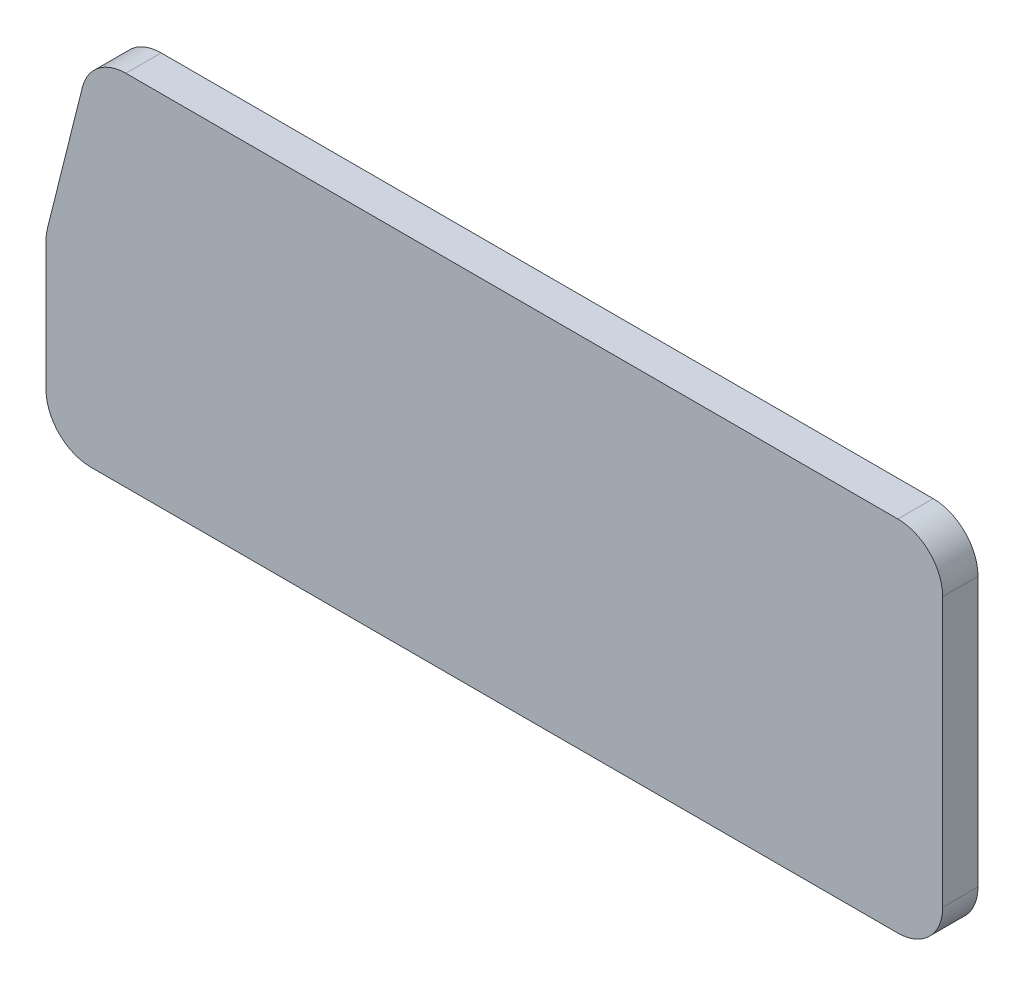
SolidWorks part; units mm, degrees
material "Oak"
ref_plane "Front Plane" through (0, 0, 0) normal (0, 0, 1) x (1, 0, 0)
ref_plane "Top Plane" through (0, 0, 0) normal (0, 1, 0) x (1, 0, 0)
ref_plane "Right Plane" through (0, 0, 0) normal (1, 0, 0) x (0, 0, -1)
sketch "Sketch1" plane through (0, 0, 0) normal (0, 0, 1) x (1, 0, 0)
  line L0 (-63.5, 0) -> (-57.15, 25.4)
  line L1 (-63.5, -25.4) -> (63.5, -25.4)
  line L2 (-63.5, -25.4) -> (-63.5, 0)
  line L3 (-57.15, 25.4) -> (63.5, 25.4)
  line L4 (63.5, -25.4) -> (63.5, 25.4)
  line L5 (-63.5, -25.4) -> (63.5, 25.4) construction
  line L6 (-57.7273, 23.0909) -> (63.5, -25.4) construction
  point P0 (0, 0)
  dimension "D1" = 50.8
  dimension "D2" = 127
  dimension "D3" = 6.35
extrude "Boss-Extrude1" add sketch "Sketch1" along normal mid plane 5
fillet "Fillet1" radius 6.35 5 edges at (63.5, 25.4, 0) (63.5, -25.4, 0) (-63.5, -25.4, 0) (-57.15, 25.4, 0) (-63.5, 0, 0)
